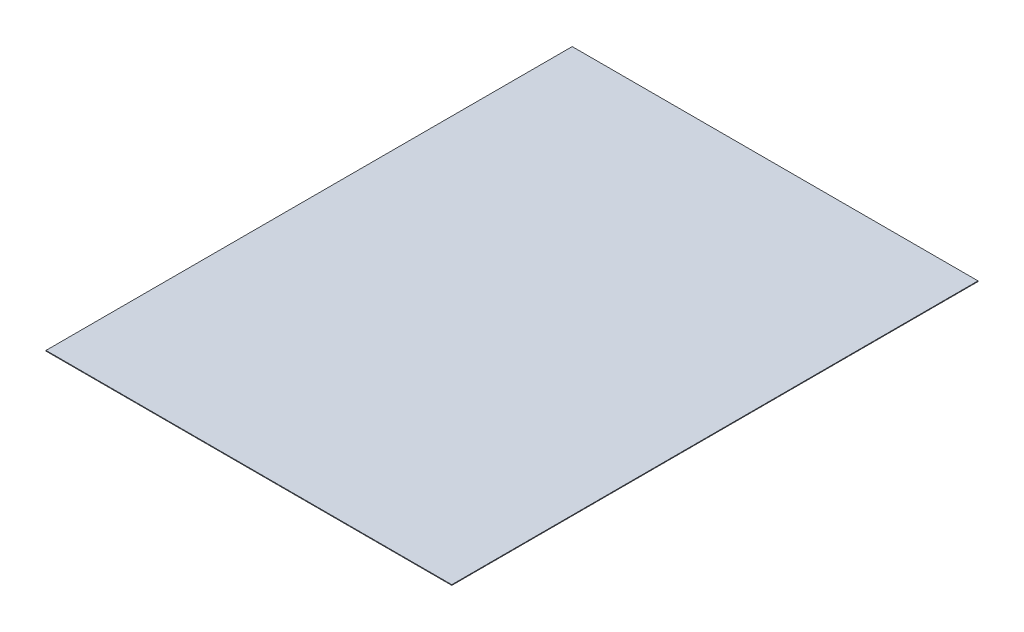
SolidWorks part; units mm, degrees
ref_plane "Front Plane" through (0, 0, 0) normal (0, 0, 1) x (1, 0, 0)
ref_plane "Top Plane" through (0, 0, 0) normal (0, 1, 0) x (1, 0, 0)
ref_plane "Right Plane" through (0, 0, 0) normal (1, 0, 0) x (0, 0, -1)
other "Configuration Table"
sketch "Sketch1" plane through (0, 0, 0) normal (0, 0, 1) x (1, 0, 0)
  line L1 (42.5, 1967.5) -> (657.5, 1967.5)
  line L2 (42.5, 1967.5) -> (42.5, 1968.5)
  line L3 (42.5, 1968.5) -> (657.5, 1968.5)
  line L4 (657.5, 1967.5) -> (657.5, 1968.5)
extrude "TOPPING_ic_tavan_1" add sketch "Sketch1" against normal blind 797.5 separate body
